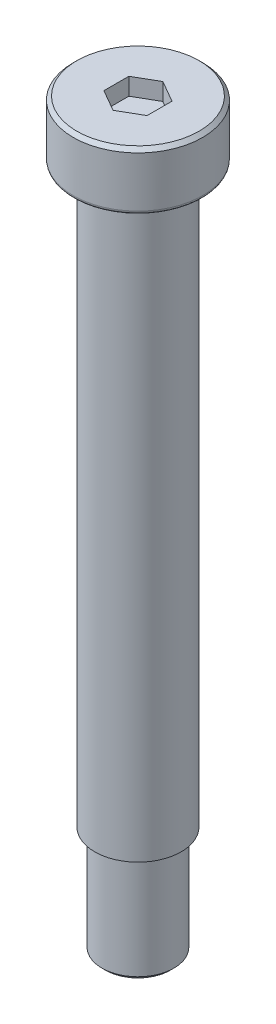
SolidWorks part; units mm, degrees
material "Plain Carbon Steel"
ref_plane "Front Plane" through (0, 0, 0) normal (0, 0, 1) x (1, 0, 0)
ref_plane "Top Plane" through (0, 0, 0) normal (0, 1, 0) x (1, 0, 0)
ref_plane "Right Plane" through (0, 0, 0) normal (1, 0, 0) x (0, 0, -1)
sketch "Sketch1" plane through (0, 0, 0) normal (0, 0, 1) x (1, 0, 0)
  line L0 (0, 0) -> (9, 0)
  line L1 (9, 0) -> (9, -8)
  line L2 (9, -8) -> (5.75, -8)
  line L3 (5.75, -8) -> (5.75, -8.5)
  line L4 (5.75, -8.5) -> (6, -8.5)
  line L5 (6, -8.5) -> (6, -88)
  line L6 (6, -88) -> (5, -88)
  line L7 (5, -88) -> (5, -103)
  line L8 (5, -103) -> (0, -103)
  line L9 (0, -103) -> (0, 0)
  line L10 (0, 5) -> (0, -108) construction
  dimension "D1" = 5
  dimension "D2" = 5
  dimension "D3" = 10
  dimension "D4" = 12
  dimension "D5" = 0.25
  dimension "D6" = 18
  dimension "Length" = 80
  dimension "D8" = 8
  dimension "D9" = 0.5
  dimension "D10" = 15
revolve "Revolve1" add sketch "Sketch1" angle 360 about L10
sketch "Sketch2" plane through (0, 0, 0) normal (0, 1, 0) x (1, 0, 0)
  line L1 (0, -3.4641) -> (3, -1.7321)
  line L2 (3, -1.7321) -> (3, 1.7321)
  line L3 (3, 1.7321) -> (0, 3.4641)
  line L4 (0, 3.4641) -> (-3, 1.7321)
  line L5 (-3, 1.7321) -> (-3, -1.7321)
  line L6 (-3, -1.7321) -> (0, -3.4641)
  circle A0 centre (0, 0) radius 3 construction
  dimension "D1" = 6
extrude "Cut-Extrude1" cut sketch "Sketch2" against normal blind 2.4
chamfer "Chamfer1" distance 0.5 angle 45 1 edges at (-9, 0, 0)
fillet "Fillet1" radius 0.5 1 edges at (-9, -8, 0)
chamfer "Chamfer2" distance 0.5 angle 45 1 edges at (-5, -103, 0)
